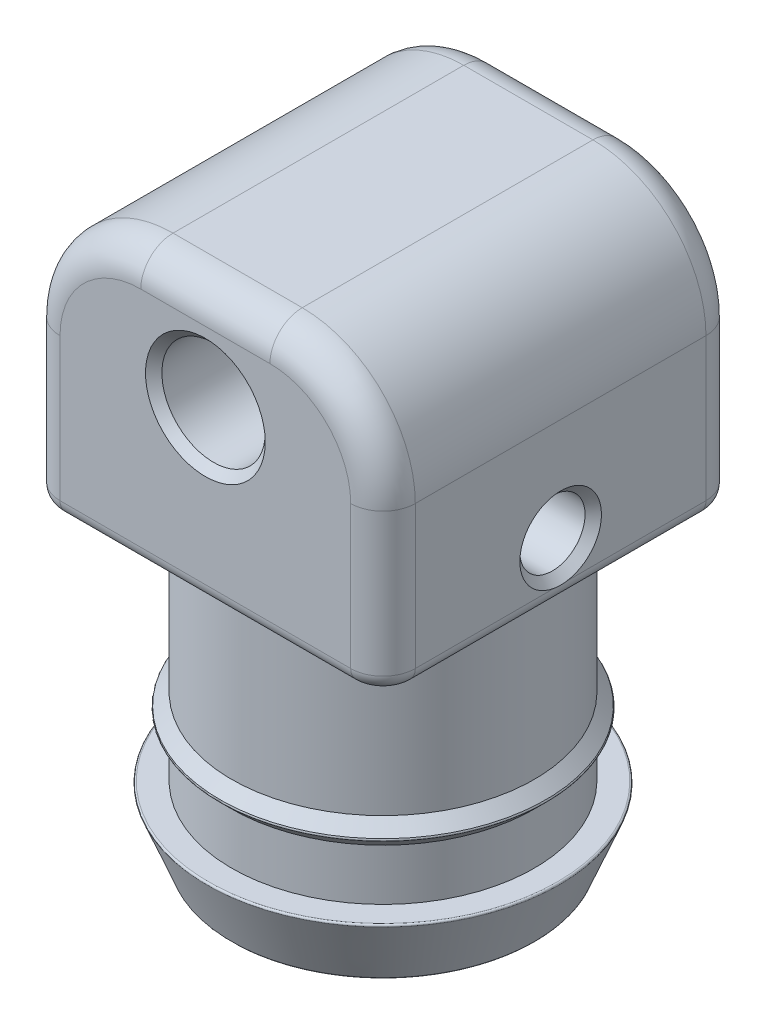
SolidWorks part; units mm, degrees
ref_plane "Front Plane" through (0, 0, 0) normal (0, 0, 1) x (1, 0, 0)
ref_plane "Top Plane" through (0, 0, 0) normal (0, 1, 0) x (1, 0, 0)
ref_plane "Right Plane" through (0, 0, 0) normal (1, 0, 0) x (0, 0, -1)
sketch "Sketch1" plane through (0, 0, 0) normal (0, 0, 1) x (1, 0, 0)
  line L3 (0, 0) -> (0, -10.5) construction
  line L4 (-11, 0) -> (-6.35, 0)
  line L5 (-11, 0) -> (-11, -10.5)
  line L6 (-11, -10.5) -> (11, -10.5)
  line L7 (11, 0) -> (11, -10.5)
  line L8 (6.35, 0) -> (11, 0)
  line L9 (11, 0) -> (11, 6.35)
  line L10 (11, 6.35) -> (-11, 6.35)
  line L11 (-11, 6.35) -> (-11, 0)
  circle A0 centre (0, 0) radius 3.2
  arc A1 (6.35, 0) -> (-6.35, 0) centre (0, 0) ccw
  dimension "D1" = 6.4
  dimension "D2" = 12.7
  dimension "D4" = 22
  dimension "D5" = 10.5
extrude "Boss-Extrude1" add sketch "Sketch1" along normal mid plane 22
sketch3d "3DSketch1" plane through (0, 0, 0) normal (0, 0, 1) x (1, 0, 0)
  dimension "D1" = 12.7
sketch "Sketch2" plane through (0, 0, 0) normal (0, 0, 1) x (1, 0, 0)
  line L0 (0, 9.544) -> (0, -9.544) construction
  line L1 (0, -10) -> (9.365, -10)
  line L4 (0, -29.5) -> (9.365, -29.5)
  line L10 (0, -29.5) -> (0, -10)
  line L11 (9.365, -29.5) -> (10.9525, -25.5312)
  line L12 (10.9525, -25.5312) -> (9.365, -25.5312)
  line L13 (9.365, -25.5312) -> (9.365, -22.3562)
  line L14 (9.365, -22.3562) -> (10.1587, -21.5625)
  line L15 (10.1587, -21.5625) -> (9.365, -20.7688)
  line L16 (10.1587, -21.5625) -> (9.365, -21.5625) construction
  line L17 (9.365, -20.7688) -> (9.365, -10)
  dimension "D1" = 18.73
  dimension "D2" = 19.5
  dimension "D3" = 1.5875
  dimension "D4" = 3.9688
  dimension "D5" = 0.7937
  dimension "D6" = 7.9375
  dimension "D7" = 10
revolve "Revolve1" add sketch "Sketch2" angle 360 about L0
sketch "Sketch3" plane through (0, -29.5, 0) normal (0, -1, 0) x (1, 0, 0)
  circle A0 centre (0, 0) radius 2.3813
  dimension "D1" = 4.7625
extrude "Cut-Extrude1" cut sketch "Sketch3" against normal blind 25 contours A0
hole_wizard "#10-32 Tapped Hole1" positions "Sketch4" profile "Sketch5" tap size "#10-32" standard "ANSI Inch"
sketch "Sketch4" plane through (11, 0, 0) normal (1, 0, 0) x (0, 0, -1)
  point P0 (0, -7)
  dimension "D1" = 7
sketch "Sketch5" plane through (11, -7, 0) normal (0, 1, 0) x (0, 0, -1)
  line L0 (0, 0) -> (0, 8.6188)
  line L1 (0, 8.6188) -> (2.0193, 8.6188)
  line L2 (2.0193, 8.6188) -> (2.0193, 0)
  line L5 (2.0193, 0) -> (0, 0)
  line L11 (0, -6.35) -> (0, 107.95) construction
  dimension "Thru Tap Drill Dia." = 4.0386
  dimension "Thru Tap Drill Depth" = 8.6188
cosmetic thread "Hole Thread1" parameters "D2"=4.826
fillet "Fillet3" radius 0.0992 6 edges at (-10.9525, -25.5312, 0) (-10.1587, -21.5625, 0) (2.3813, -29.5, 0) (2.3813, -4.5, 0) (2.3577, -8.9915, -0.3339) (-9.365, -29.5, 0)
chamfer "Chamfer1" distance 0.508 angle 45 3 edges at (11, -7, -2.0193) (3.2, 0, 11) (3.2, 0, -11)
fillet "Fillet4" radius 7 2 edges at (11, 6.35, 0) (-11, 6.35, 0)
fillet "Fillet5" radius 2 10 edges at (11, -5.575, -11) (11, -5.575, 11) (8.9497, 4.2997, 11) (8.9497, 4.2997, -11) (0, 6.35, 11) (0, 6.35, -11) (-8.9497, 4.2997, 11) (-8.9497, 4.2997, -11) (-11, -5.575, 11) (-11, -5.575, -11)
fillet "Fillet6" radius 1 8 edges at (-10.4142, -10.5, 10.4142) (0, -10.5, 11) (10.4142, -10.5, 10.4142) (11, -10.5, 0) (10.4142, -10.5, -10.4142) (0, -10.5, -11) (-10.4142, -10.5, -10.4142) (-11, -10.5, 0)
